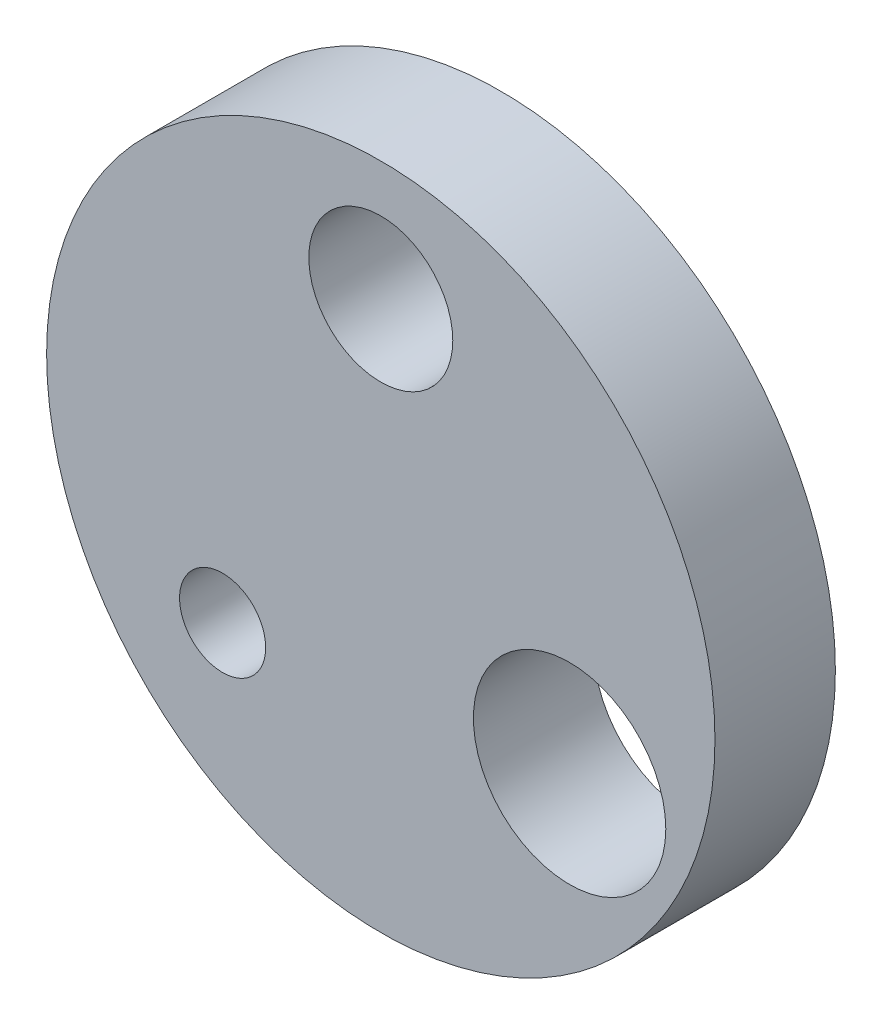
SolidWorks part; units mm, degrees
ref_plane "Alzado" through (0, 0, 0) normal (0, 0, 1) x (1, 0, 0)
ref_plane "Planta" through (0, 0, 0) normal (0, 1, 0) x (1, 0, 0)
ref_plane "Vista lateral" through (0, 0, 0) normal (1, 0, 0) x (0, 0, -1)
sketch "Croquis1" plane through (0, 0, 0) normal (0, 0, 1) x (1, 0, 0)
  circle A0 centre (0, 0) radius 55.5
  circle A1 centre (0, 35.6359) radius 11.9553
  circle A2 centre (0, 0) radius 35.6359 construction
  circle A3 centre (-26.2688, -24.0804) radius 7.1498
  circle A4 centre (31.3572, -16.9306) radius 15.976
  dimension "D1" = 111
extrude "Saliente-Extruir1" add sketch "Croquis1" along normal blind 20
